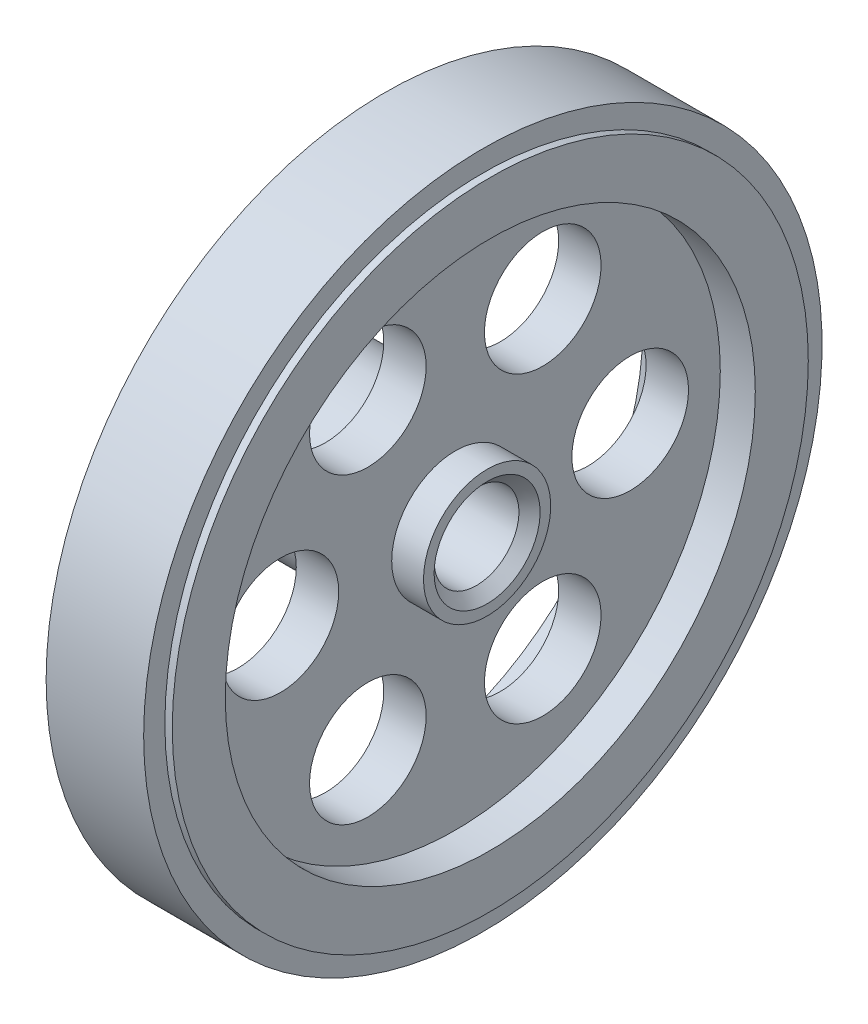
SolidWorks part; units mm, degrees
ref_plane "Front Plane" through (0, 0, 0) normal (0, 0, 1) x (1, 0, 0)
ref_plane "Top Plane" through (0, 0, 0) normal (0, 1, 0) x (1, 0, 0)
ref_plane "Right Plane" through (0, 0, 0) normal (1, 0, 0) x (0, 0, -1)
sketch "Sketch1" plane through (0, 0, 0) normal (0, 1, 0) x (1, 0, 0)
  line L0 (0, 0) -> (17, 0) construction
  line L1 (17, 4) -> (0, 4)
  line L2 (0, 4) -> (0, 8)
  line L3 (0, 8) -> (10, 8)
  line L4 (10, 8) -> (10, 25)
  line L5 (10, 25) -> (6.7, 25)
  line L6 (6.7, 25) -> (6.7, 30)
  line L7 (6.7, 30) -> (7.4, 30)
  line L8 (7.4, 30) -> (7.4, 32)
  line L9 (7.4, 32) -> (16.6, 32)
  line L10 (12, 32) -> (12, 4) construction
  line L11 (16.6, 30) -> (16.6, 32)
  line L12 (17.3, 30) -> (16.6, 30)
  line L13 (17.3, 25) -> (17.3, 30)
  line L14 (14, 25) -> (17.3, 25)
  line L15 (14, 25) -> (14, 6)
  line L16 (14, 6) -> (17, 6)
  line L17 (17, 6) -> (17, 4)
  dimension "D1" = 4
  dimension "D2" = 8
  dimension "D3" = 10
  dimension "D4" = 25
  dimension "D5" = 5
  dimension "D6" = 10.6
  dimension "D7" = 32
  dimension "D8" = 9.2
  dimension "D9" = 4
  dimension "D10" = 3
  dimension "D11" = 6
revolve "Revolve1" add sketch "Sketch1" angle 360 about L0
chamfer "Chamfer1" distance 1 angle 45 2 edges at (0, 0, 4) (17, 0, 4)
sketch "Sketch2" plane through (14, 0, 0) normal (1, 0, 0) x (0, 0, -1)
  line L0 (0, 0) -> (-16.5, 0) construction
  circle A0 centre (-16.5, 0) radius 5.5
  circle A1 centre (-8.25, 14.2894) radius 5.5
  circle A2 centre (8.25, 14.2894) radius 5.5
  circle A3 centre (16.5, 0) radius 5.5
  circle A4 centre (8.25, -14.2894) radius 5.5
  circle A5 centre (-8.25, -14.2894) radius 5.5
  point P16 (0, 0)
  dimension "D1" = 11
  dimension "D2" = 16.5
  dimension "D3" = 6
extrude "Cut-Extrude1" cut sketch "Sketch2" against normal through all and the other way through all
